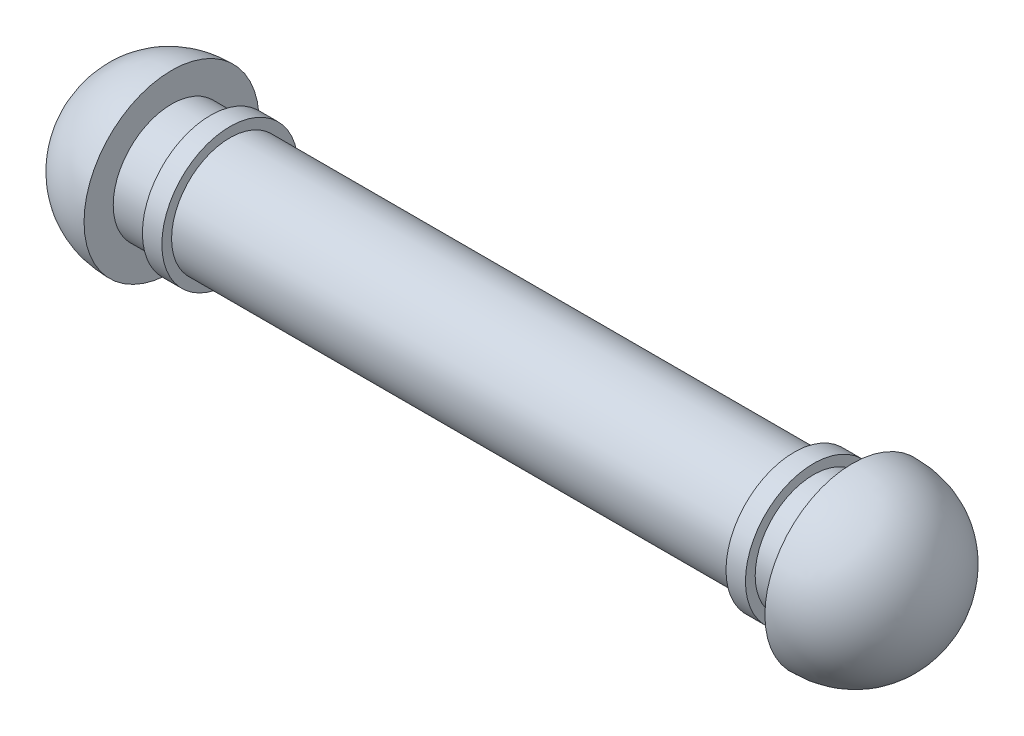
SolidWorks part; units mm, degrees
ref_plane "Front Plane" through (0, 0, 0) normal (0, 0, 1) x (1, 0, 0)
ref_plane "Top Plane" through (0, 0, 0) normal (0, 1, 0) x (1, 0, 0)
ref_plane "Right Plane" through (0, 0, 0) normal (1, 0, 0) x (0, 0, -1)
sketch "Sketch1" plane through (0, 0, 0) normal (1, 0, 0) x (0, 0, -1)
  circle A0 centre (0, 0) radius 30
  dimension "D1" = 60
extrude "Boss-Extrude1" add sketch "Sketch1" along normal blind 175
sketch "Sketch3" plane through (0, 0, 0) normal (0, 0, 1) x (1, 0, 0)
  line L0 (20, 0) -> (20, 35)
  line L2 (-100.0787, 0) -> (83.5342, 0) construction
  line L3 (0, 0) -> (-45.4584, 0)
  line L4 (0, 45) -> (0, 0)
  line L5 (20, 35) -> (30, 35)
  line L6 (30, 35) -> (30, 0)
  line L7 (20, 0) -> (30, 0)
  spline S0 degree 3 poles (-45.4584, 0) (-45.4584, 20.1838) (-30.9912, 45) (0, 45) knots 0 0 0 0 1 1 1 1
  dimension "D1" = 45
  dimension "D2" = 20
  dimension "D3" = 10
  dimension "D4" = 35
revolve "Revolve1" add sketch "Sketch3" angle 360 about L2
mirror "Mirror1" about plane through (175, 0, 0) normal (1, 0, 0) of "Boss-Extrude1", "Revolve1"
